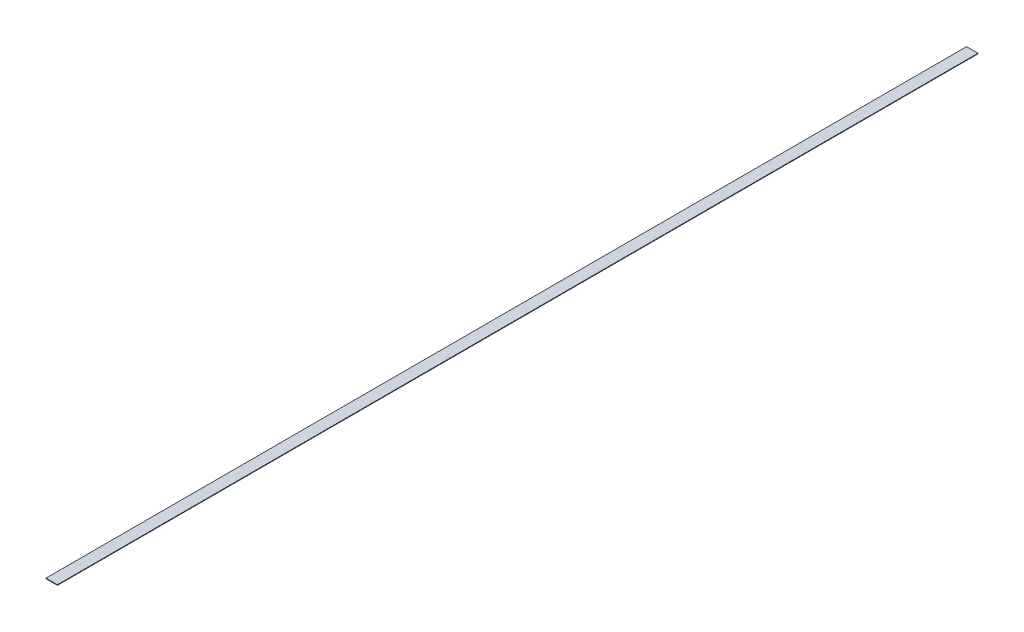
SolidWorks part; units mm, degrees
ref_plane "前视基准面" through (0, 0, 0) normal (0, 0, 1) x (1, 0, 0)
ref_plane "上视基准面" through (0, 0, 0) normal (0, 1, 0) x (1, 0, 0)
ref_plane "右视基准面" through (0, 0, 0) normal (1, 0, 0) x (0, 0, -1)
sketch "草图1" plane through (0, 0, 0) normal (0, 1, 0) x (1, 0, 0)
  line L0 (-398.7506, 807.1628) -> (-398.7506, -805.2887) construction
  line L1 (-398.7506, -805.2887) -> (401.2494, -805.2887) construction
  line L2 (401.2494, -805.2887) -> (401.2494, 807.1628) construction
  line L3 (401.2494, 807.1628) -> (-398.7506, 807.1628) construction
  line L4 (1.2494, 807.1628) -> (1.2494, -805.2887) construction
  line L5 (-8.7506, 807.1628) -> (-8.7506, -805.2887)
  line L6 (11.2494, 807.1628) -> (11.2494, -805.2887)
  line L7 (-8.7506, 807.1628) -> (11.2494, 807.1628)
  line L8 (-8.7506, -805.2887) -> (11.2494, -805.2887)
  dimension "D1" = 10
  dimension "D2" = 10
extrude "凸台-拉伸1" add sketch "草图1" along normal blind 1
